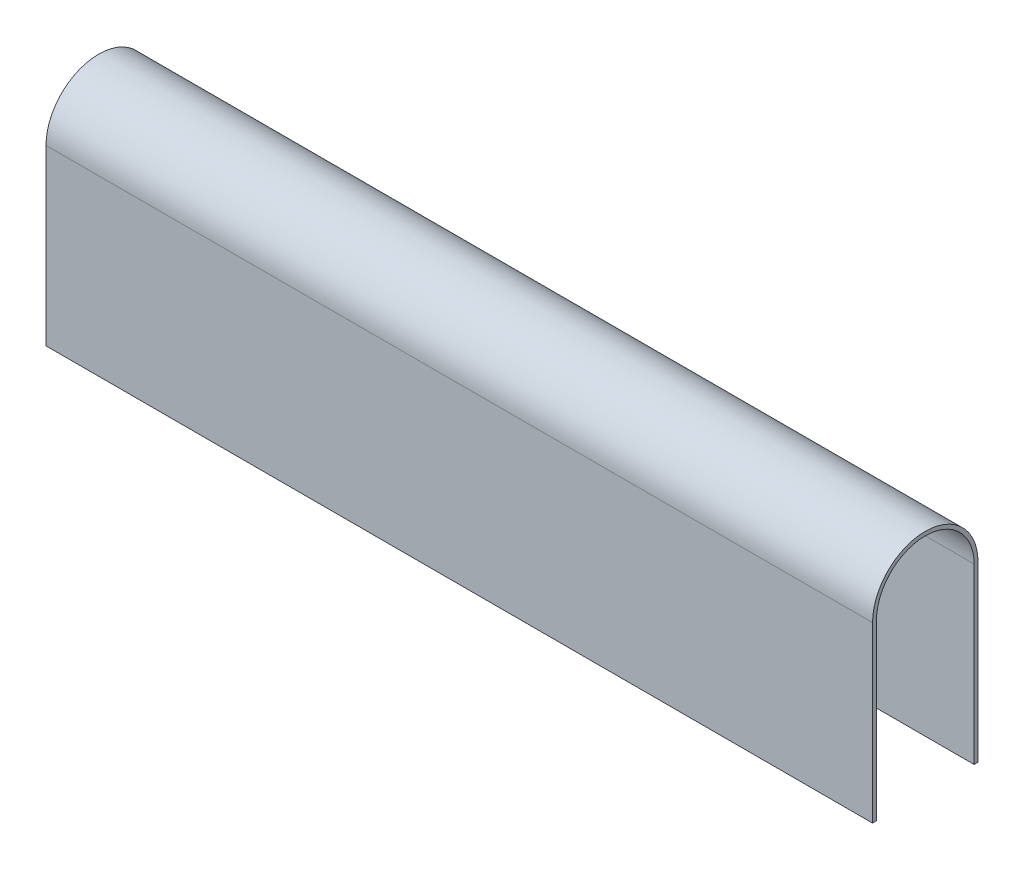
SolidWorks part; units mm, degrees
material "AISI 1020"
ref_plane "Front Plane" through (0, 0, 0) normal (0, 0, 1) x (1, 0, 0)
ref_plane "Top Plane" through (0, 0, 0) normal (0, 1, 0) x (1, 0, 0)
ref_plane "Right Plane" through (0, 0, 0) normal (1, 0, 0) x (0, 0, -1)
sketch "Sketch1" plane through (0, 0, 0) normal (1, 0, 0) x (0, 0, -1)
  line L0 (-30.099, 67.7418) -> (-30.099, 0)
  line L1 (-30.099, 0) -> (-28.575, 0)
  line L2 (-28.575, 67.7418) -> (-28.575, 0)
  line L4 (9.525, 67.7418) -> (9.525, 0)
  line L5 (11.049, 67.7418) -> (11.049, 0)
  line L6 (11.049, 0) -> (9.525, 0)
  arc A0 (9.525, 67.7418) -> (-28.575, 67.7418) centre (-9.525, 67.7418) ccw
  arc A1 (11.049, 67.7418) -> (-30.099, 67.7418) centre (-9.525, 67.7418) ccw
  dimension "D1" = 38.1
  dimension "D4" = 41.148
  dimension "D2" = 67.7418
  dimension "D3" = 38.1
extrude "Boss-Extrude1" add sketch "Sketch1" along normal blind 322.5133
